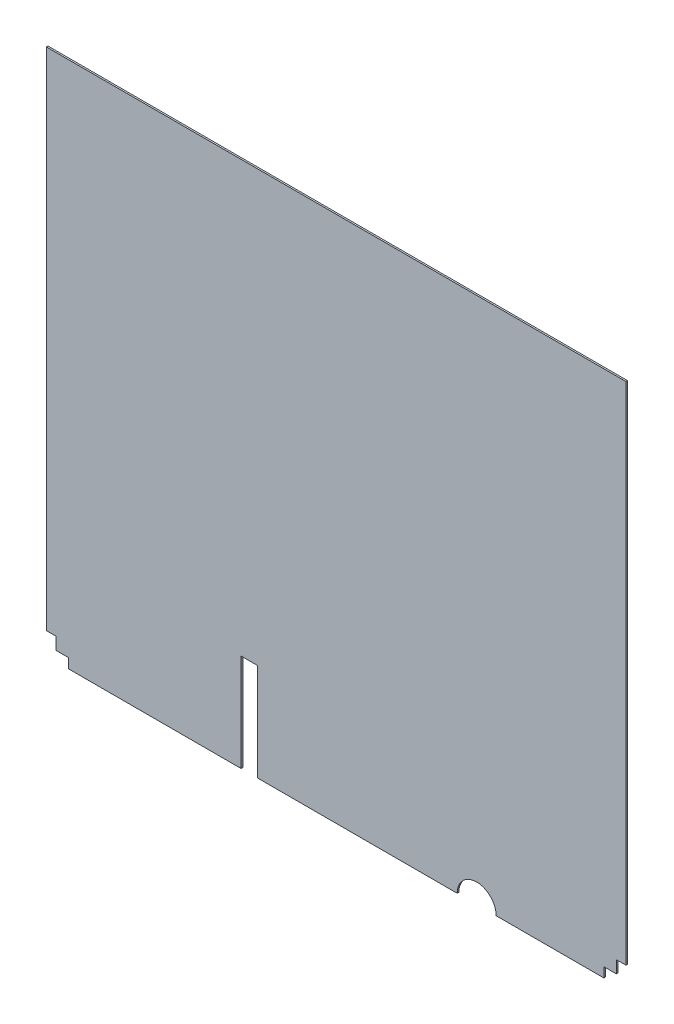
SolidWorks part; units mm, degrees
ref_plane "Front Plane" through (0, 0, 0) normal (0, 0, 1) x (1, 0, 0)
ref_plane "Top Plane" through (0, 0, 0) normal (0, 1, 0) x (1, 0, 0)
ref_plane "Right Plane" through (0, 0, 0) normal (1, 0, 0) x (0, 0, -1)
sketch "Sketch1" plane through (0, 0, 0) normal (0, 0, 1) x (1, 0, 0)
  line L0 (0, 34.544) -> (15.24, 34.544)
  line L1 (0, 0) -> (907.001, 0)
  line L2 (0, 0) -> (0, 825.5)
  line L3 (0, 825.5) -> (907.001, 825.5)
  line L4 (907.001, 0) -> (907.001, 825.5)
  line L5 (0, 0) -> (914.4, 0) construction
  line L6 (0, 0) -> (0, 914.4) construction
  line L7 (0, 914.4) -> (914.4, 914.4) construction
  line L8 (914.4, 0) -> (914.4, 914.4) construction
  line L9 (15.24, 34.544) -> (15.24, 15.24)
  line L10 (15.24, 15.24) -> (34.544, 15.24)
  line L11 (34.544, 15.24) -> (34.544, 0)
  line L12 (907.001, 34.544) -> (891.761, 34.544)
  line L13 (891.761, 34.544) -> (891.761, 15.24)
  line L14 (891.761, 15.24) -> (872.457, 15.24)
  line L15 (872.457, 15.24) -> (872.457, 0)
  line L16 (304.8, 0) -> (304.8, 152.4)
  line L17 (304.8, 152.4) -> (330.2, 152.4)
  line L18 (330.2, 152.4) -> (330.2, 0)
  arc A0 (703.801, 0) -> (642.841, 0) centre (673.321, 0) ccw
  dimension "D13" = 30.48
  dimension "D1" = 825.5
  dimension "D2" = 907.001
  dimension "D3" = 914.4
  dimension "D4" = 914.4
  dimension "D5" = 15.24
  dimension "D6" = 15.24
  dimension "D7" = 34.544
  dimension "D8" = 34.544
  dimension "D9" = 15.24
  dimension "D10" = 15.24
  dimension "D11" = 34.544
  dimension "D12" = 34.544
  dimension "D14" = 152.4
  dimension "D15" = 25.4
  dimension "D16" = 203.2
  dimension "D17" = 304.8
extrude "Boss-Extrude1" add sketch "Sketch1" along normal blind 2.54 contours L15 L14 L13 L12 L4 L3 L2 L0 L9 L10 L11 L1
